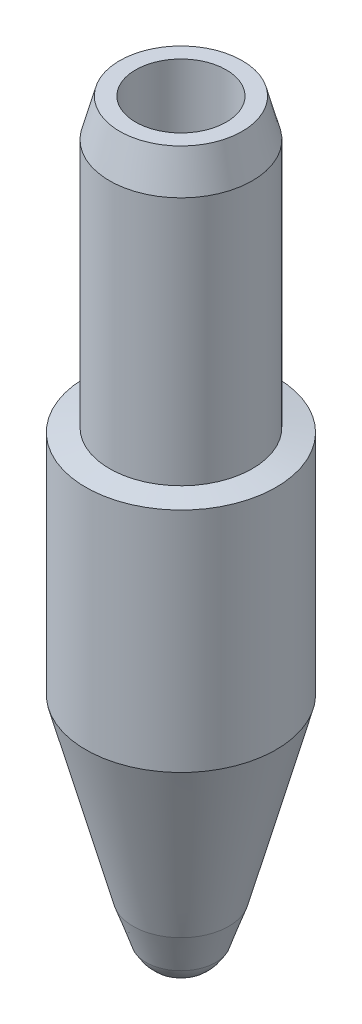
SolidWorks part; units mm, degrees
material "Titânio Ti-5Al-2.5Sn"
ref_plane "Plano frontal" through (0, 0, 0) normal (0, 0, 1) x (1, 0, 0)
ref_plane "Plano superior" through (0, 0, 0) normal (0, 1, 0) x (1, 0, 0)
ref_plane "Plano direito" through (0, 0, 0) normal (1, 0, 0) x (0, 0, -1)
sketch "Esboço1" plane through (0, 0, 0) normal (0, 0, 1) x (1, 0, 0)
  line L0 (0, 0) -> (0, 13.97) construction
  line L1 (0, 0) -> (0.4621, 0) construction
  line L2 (0.634, 0.5) -> (1.26, 2.8364)
  line L3 (1.26, 2.8364) -> (1.26, 5.8445)
  line L7 (0.945, 5.9) -> (0.945, 9.2)
  line L8 (0.945, 9.2) -> (0.811, 9.7)
  line L10 (0.811, 9.7) -> (0.6, 9.7)
  line L11 (0.6, 9.7) -> (0.6, 4.2)
  line L12 (0.6, 4.2) -> (0.45, 4.1134)
  line L13 (0.45, 4.1134) -> (0.45, 1.7)
  line L14 (0.45, 1.7) -> (0, 1.4402) construction
  line L15 (0, 1.4402) -> (0, 0) construction
  line L17 (0.4621, 0) -> (0.634, 0.5)
  line L18 (0.945, 5.9) -> (1.26, 5.8445)
  line L19 (0.45, 1.7) -> (0.1502, 0)
  line L20 (0.1502, 0) -> (0.4621, 0)
  circle A0 centre (0, 0.2) radius 0.5 construction
  dimension "D22" = 1
  dimension "D23" = 0.2
  dimension "D2" = 60
  dimension "D3" = 0.9
  dimension "D4" = 60
  dimension "D5" = 9.7
  dimension "D6" = 15
  dimension "D7" = 1.7
  dimension "D8" = 3.8
  dimension "D9" = 1.2
  dimension "D10" = 0.5
  dimension "D11" = 10
  dimension "D12" = 5.5866
  dimension "D13" = 0.9242
  dimension "D14" = 0.5
  dimension "D15" = 18.969
  dimension "D16" = 10
  dimension "D17" = 15
  dimension "D18" = 2.52
  dimension "D21" = 1.89
revolve "Revolução1" add sketch "Esboço1" angle 360 about L0
sketch "Esboço2" plane through (0, 0, 0) normal (0, 0, 1) x (1, 0, 0)
  line L0 (0, 0.7) -> (0, -0.3)
  circle A0 centre (0, 0.2) radius 0.5 construction
  arc A1 (0, -0.3) -> (0, 0.7) centre (0, 0.2) ccw
revolve "Revolução2" add sketch "Esboço2" angle 360 about L0
